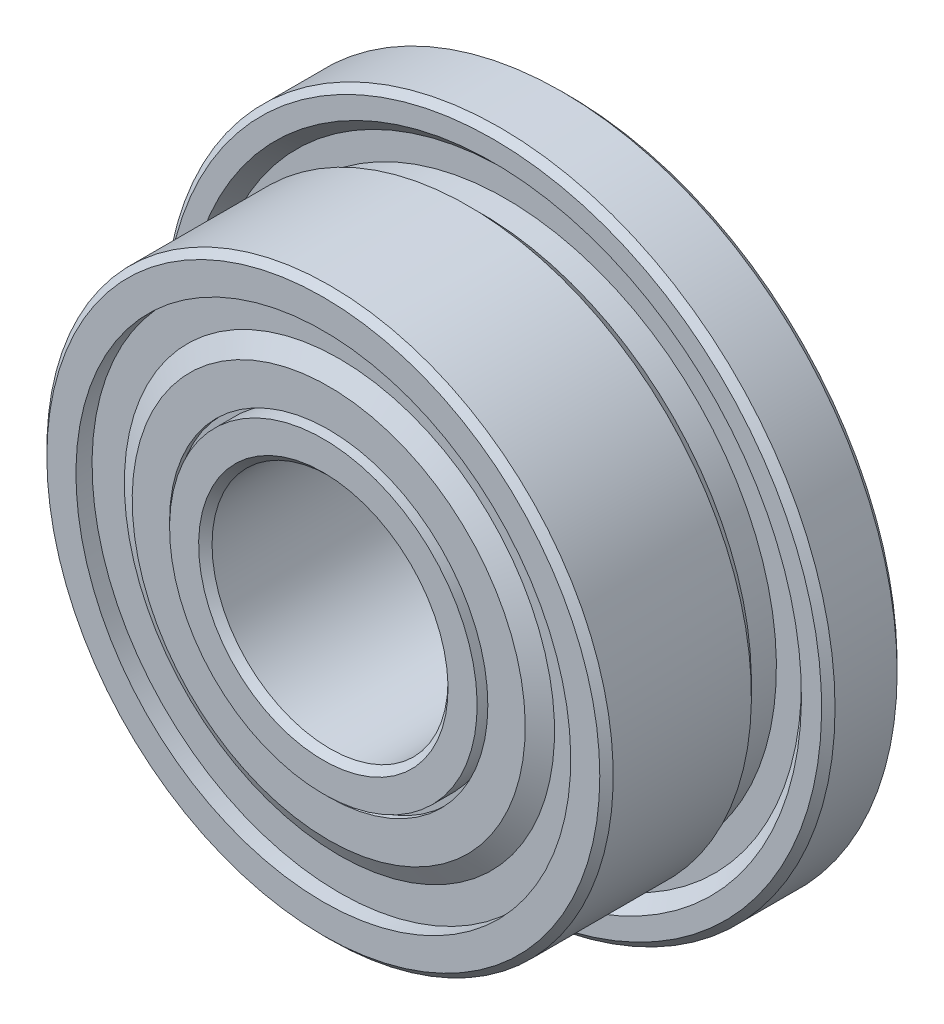
SolidWorks part; units mm, degrees
ref_plane "Front Plane" through (0, 0, 0) normal (0, 0, 1) x (1, 0, 0)
ref_plane "Top Plane" through (0, 0, 0) normal (0, 1, 0) x (1, 0, 0)
ref_plane "Right Plane" through (0, 0, 0) normal (1, 0, 0) x (0, 0, -1)
sketch "Sketch1" plane through (0, 0, 0) normal (1, 0, 0) x (0, 0, -1)
  line L0 (0, 3) -> (0, -3) construction
  line L1 (-1.3, 3) -> (1.3, 3) construction
  line L2 (0, 0) -> (1.3, 0) construction
  line L3 (1.3, 3.55) -> (1.3, -3.55) construction
  line L4 (1.3, -3.55) -> (0.5, -3.55) construction
  line L5 (1.3, 1.25) -> (0, 1.25) construction
  line L6 (1.3, 1.25) -> (1.3, -1.25) construction
  dimension "OD" = 6
  dimension "Width" = 2.6
  dimension "Flange Thickness" = 0.8
  dimension "ID" = 2.5
  dimension "Flange OD" = 7.1
sketch "Sketch2" plane through (0, 0, 0) normal (1, 0, 0) x (0, 0, -1)
  line L0 (1.3, 3.55) -> (0.5, 3.55)
  line L1 (0.5, 3.55) -> (0.5, 3.2652)
  line L2 (0.2348, 3) -> (-1.3, 3)
  line L3 (-1.3, 3) -> (-1.3, 2.4313)
  line L4 (-1.3, 2.4313) -> (-0.2573, 2.4313)
  line L5 (1.3, 3.55) -> (1.3, -3.55) construction
  line L6 (1.3, 2.4313) -> (1.3, 3.55)
  line L7 (1.3, 1.25) -> (-1.3, 1.25)
  line L8 (-1.3, 1.25) -> (-1.3, 1.8188)
  line L9 (-1.3, 1.8188) -> (-0.2573, 1.8188)
  line L10 (1.3, 1.8188) -> (1.3, 1.25)
  line L11 (0, 3) -> (0, 1.25) construction
  line L12 (-0.4, 2.125) -> (0.4, 2.125) construction
  line L13 (0.2573, 2.4313) -> (1.3, 2.4313)
  line L14 (0.2573, 1.8188) -> (1.3, 1.8188)
  line L15 (0.5, 3.2652) -> (0.6326, 3.1326)
  line L16 (0.6326, 3.1326) -> (0.6326, 2.8674)
  line L17 (0.6326, 2.8674) -> (0.3674, 2.8674)
  line L18 (0.3674, 2.8674) -> (0.2348, 3)
  line L19 (0.5, 3) -> (0.6326, 2.8674) construction
  line L20 (0.6326, 3.1326) -> (0.3674, 2.8674) construction
  line L21 (0.2348, 3) -> (0.5, 3) construction
  line L22 (0.5, 3) -> (0.5, 3.2652) construction
  line L23 (-1.3, 0) -> (1.3, 0) construction
  circle A0 centre (0, 2.125) radius 0.4 construction
  arc A1 (-0.2573, 2.4313) -> (0.2573, 2.4313) centre (0, 2.125) cw
  arc A2 (-0.2573, 1.8188) -> (0.2573, 1.8188) centre (0, 2.125) ccw
  dimension "Ball Dia." = 0.8
  dimension "D2" = 135
  dimension "D3" = 0.375
  dimension "Race Thikness" = 0.5687
  dimension "D4" = 0.6125
revolve "Revolve1" add sketch "Sketch2" angle 360 about L2
fillet "Fillet1" radius 0.0711 3 edges at (0, -3.55, -1.3) (0, -3.55, -0.5) (0, -3, 1.3) profile chamfer
sketch "Sketch3" plane through (0, 0, 0) normal (0, 0, 1) x (1, 0, 0)
  line L0 (-1.25, 0) -> (1.25, 0) construction
  line L1 (-3, 0) -> (3, 0) construction
  point P5 (0, 0)
  dimension "ID2" = 2.5
  dimension "OD2" = 6
fillet "Fillet2" radius 0.0711 2 edges at (0, -1.25, -1.3) (0, -1.25, 1.3) profile chamfer
sketch "Sketch7" plane through (0, 0, 0) normal (0, 0, 1) x (1, 0, 0)
  line L0 (0, 2.525) -> (0, 1.725)
  line L1 (0, 3.55) -> (0, -3.55) construction
  line L2 (-0.4839, 2.525) -> (0, 0) construction
  line L3 (0, 0) -> (0.4839, 2.525) construction
  line L4 (0.4839, 2.525) -> (-0.4839, 2.525) construction
  circle A0 centre (0, 2.125) radius 0.4 construction
  circle A1 centre (0, 0) radius 2.525 construction
  circle A2 centre (0, 0) radius 1.725 construction
  arc A4 (0, 2.525) -> (0, 1.725) centre (0, 2.125) ccw
  dimension "D1" = 21.7
revolve "Revolve3" add sketch "Sketch7" angle 360 about L0
pattern_circular "CirPattern3" count 13 over 360 about axis through (0, 0, 0) along (0, 0, 1) of bodies 107
sketch "Sketch8" plane through (0, 0, 0) normal (1, 0, 0) x (0, 0, -1)
  line L1 (-1.3, 2.4313) -> (-1.0725, 2.4313)
  line L2 (-1.3, 2.4313) -> (-1.3, 2.6208)
  line L3 (-1.3, 2.6208) -> (-1.0725, 2.6208)
  line L4 (-1.0725, 2.4313) -> (-1.0725, 2.6208)
  line L5 (1.3, 2.4313) -> (1.0725, 2.4313)
  line L6 (1.3, 2.4313) -> (1.3, 2.6208)
  line L7 (1.3, 2.6208) -> (1.0725, 2.6208)
  line L8 (1.0725, 2.4313) -> (1.0725, 2.6208)
  line L9 (1.3, 1.8188) -> (1.0725, 1.8188)
  line L10 (1.3, 1.8188) -> (1.3, 1.6292)
  line L11 (1.3, 1.6292) -> (1.0725, 1.6292)
  line L12 (1.0725, 1.8188) -> (1.0725, 1.6292)
  line L13 (-1.3, 1.8188) -> (-1.0725, 1.8187)
  line L14 (-1.3, 1.8188) -> (-1.3, 1.6292)
  line L15 (-1.3, 1.6292) -> (-1.0725, 1.6292)
  line L16 (-1.0725, 1.8187) -> (-1.0725, 1.6292)
  dimension "D1" = 0.1896
  dimension "D2" = 0.2275
revolve "Cut-Revolve1" cut sketch "Sketch8" angle 360 about L2
sketch "Sketch9" plane through (0, 0, 0) normal (1, 0, 0) x (0, 0, -1)
  line L0 (-1.0725, 2.6208) -> (-1.0725, 2.2637)
  line L1 (-1.0725, 2.2637) -> (-1.1862, 2.0667)
  line L2 (-1.1862, 2.0667) -> (-1.1862, 1.686)
  line L3 (1.1863, 1.686) -> (1.1863, 1.6292) construction
  line L4 (1.0725, 2.6208) -> (1.0725, 2.2637)
  line L5 (1.0725, 2.2637) -> (1.1863, 2.0667)
  line L6 (1.1863, 2.0667) -> (1.1863, 1.686)
  line L7 (1.3, 1.6292) -> (1.0725, 1.6292) construction
  line L8 (-1.1294, 2.6208) -> (-1.1294, 2.2789)
  line L9 (-1.1294, 2.2789) -> (-1.2431, 2.0819)
  line L10 (-1.2431, 2.0819) -> (-1.2431, 1.686)
  line L11 (-1.0725, 2.6208) -> (-1.1294, 2.6208)
  line L12 (-1.1862, 1.686) -> (-1.2431, 1.686)
  line L13 (1.1294, 2.6208) -> (1.1294, 2.2789)
  line L14 (1.1294, 2.2789) -> (1.2431, 2.0819)
  line L15 (1.2431, 2.0819) -> (1.2431, 1.686)
  line L16 (1.0725, 2.6208) -> (1.1294, 2.6208)
  line L17 (1.1863, 1.686) -> (1.2431, 1.686)
  line L18 (-1.0725, 2.2637) -> (-1.0725, 2.5308) construction
  line L19 (1.0725, 2.2637) -> (1.0725, 2.6208) construction
  line L20 (-1.0725, 1.6292) -> (-1.3, 1.6292) construction
  line L22 (-1.1862, 1.686) -> (-1.1862, 1.6292) construction
  dimension "D2" = 150
  dimension "D1" = 150
  dimension "D5" = 0.2275
  dimension "D3" = 0.0569
  dimension "D4" = 0.0569
  dimension "D6" = 0.3571
revolve "Revolve4" add sketch "Sketch9" angle 360 about L2
equation "\"D1@Fillet1\"=\"Race Thikness@Sketch2\"/8"
equation "\"ID2@Sketch3\" = \"ID@Sketch1\""
equation "\"OD2@Sketch3\" = \"OD@Sketch1\""
equation "\"D1@Fillet2\"=\"Race Thikness@Sketch2\"/8"
equation "\"D1@CirPattern3\"=360/\"D1@Sketch7\"-4"
equation "\"D1@Sketch8\"=\"Race Thikness@Sketch2\"/3"
equation "\"D2@Sketch8\"=\"Race Thikness@Sketch2\"/2.5"
equation "\"D3@Sketch9\"=\"D5@Sketch9\"/4"
equation "\"D4@Sketch9\"=\"D5@Sketch9\"/4"
equation "\"D1@Sketch9\"=\"D2@Sketch9\""
equation "\"Ball Dia.@Sketch2\" = \"D1@Sketch2\"*.5"
equation "\"D4@Sketch2\"=((\"OD@Sketch1\"-\"ID@Sketch1\")/2)*.35"
